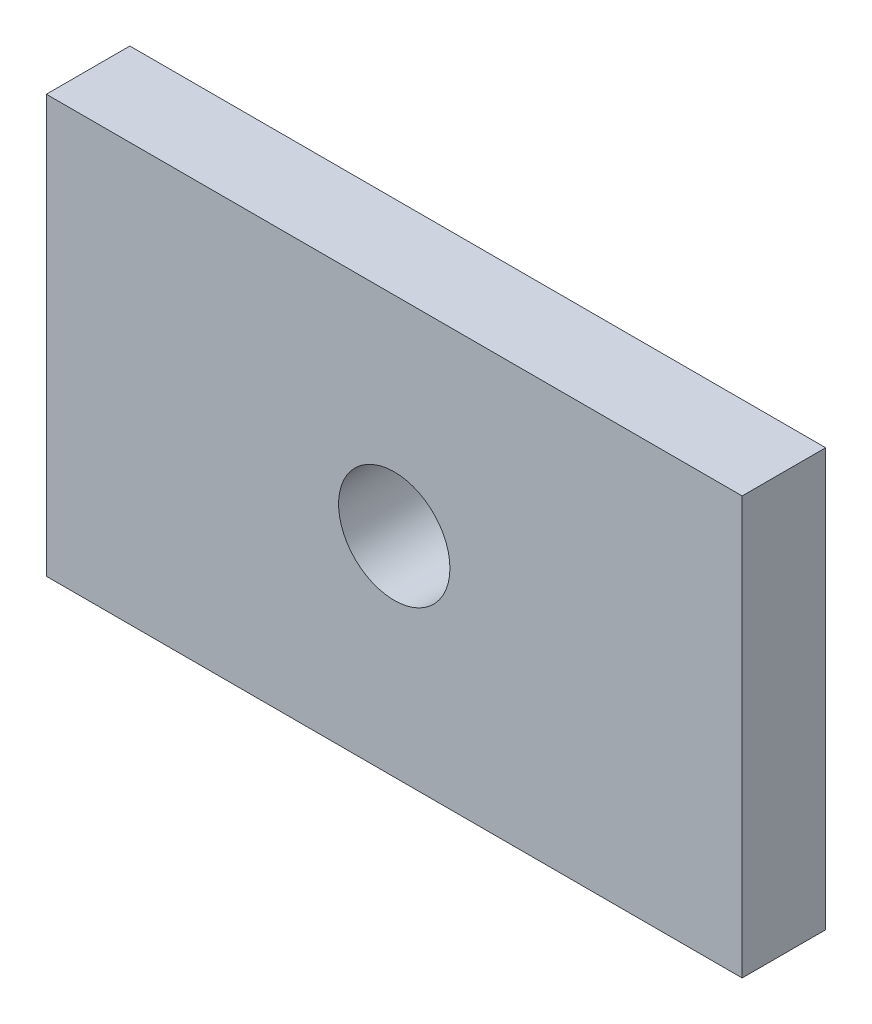
SolidWorks part; units mm, degrees
ref_plane "Front Plane" through (0, 0, 0) normal (0, 0, 1) x (1, 0, 0)
ref_plane "Top Plane" through (0, 0, 0) normal (0, 1, 0) x (1, 0, 0)
ref_plane "Right Plane" through (0, 0, 0) normal (1, 0, 0) x (0, 0, -1)
sketch "Sketch1" plane through (0, 0, 0) normal (0, 0, 1) x (1, 0, 0)
  line L0 (-25, 15) -> (0, 0) construction
  line L1 (0, 0) -> (-25, 0)
  line L2 (0, 0) -> (0, 15)
  line L3 (0, 15) -> (-25, 15)
  line L4 (-25, 0) -> (-25, 15)
  line L5 (0, 15) -> (-25, 0) construction
  circle A0 centre (-12.5, 7.5) radius 2
  dimension "D3" = 4
  dimension "D1" = 15
  dimension "D2" = 25
extrude "Boss-Extrude1" add sketch "Sketch1" along normal blind 3
